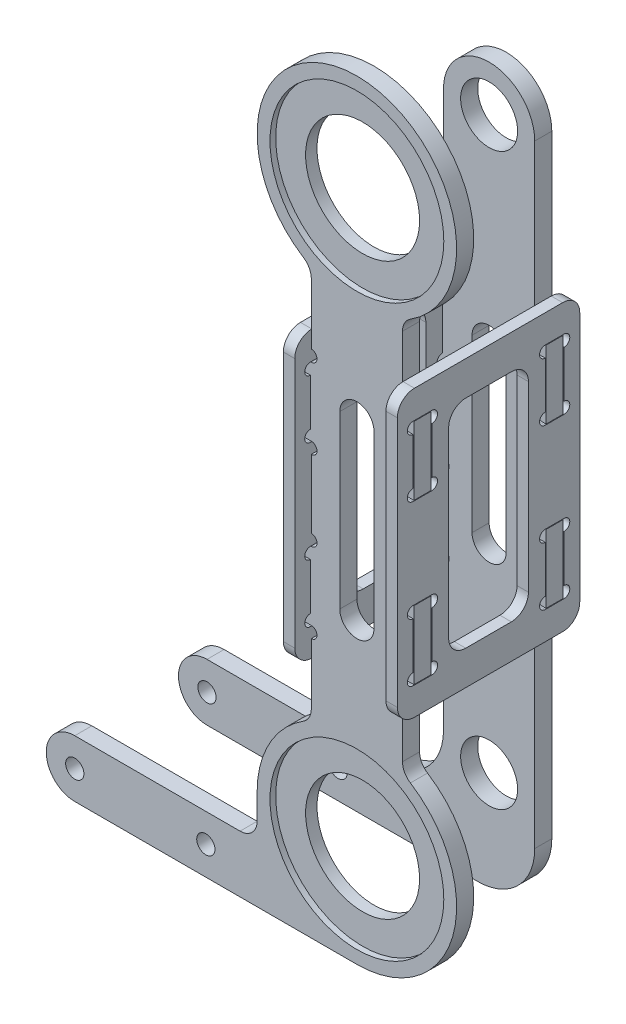
SolidWorks part; units mm, degrees
material "碳板"
ref_plane "前视基准面" through (0, 0, 0) normal (0, 0, 1) x (1, 0, 0)
ref_plane "上视基准面" through (0, 0, 0) normal (0, 1, 0) x (1, 0, 0)
ref_plane "右视基准面" through (0, 0, 0) normal (1, 0, 0) x (0, 0, -1)
sketch "草图1" plane through (0, 0, 0) normal (0, 0, 1) x (1, 0, 0)
  line L0 (-20.9655, 0) -> (46.7145, 0) construction
  line L1 (0, 28.1931) -> (0, -16.3862) construction
  line L2 (0, 5) -> (32, 5)
  line L3 (0, -5) -> (49.5, -5)
  line L4 (32, 5) -> (32, 12.5)
  line L5 (49.5, 12.5) -> (49.5, 117.1488) construction
  line L6 (41.5, 96.9356) -> (41.5, 84.5)
  line L7 (57.5, 96.9356) -> (57.5, 84.5)
  line L8 (41.5, 62.5) -> (57.5, 62.5) construction
  line L9 (41.5, 82.5) -> (39.5, 82.5)
  line L10 (39.5, 82.5) -> (39.5, 70.5)
  line L11 (39.5, 70.5) -> (41.5, 70.5)
  line L12 (49.5, 47.5) -> (49.5, 77.5) construction
  line L13 (41.5, 68.5) -> (41.5, 56.5)
  line L14 (59.5, 70.5) -> (57.5, 70.5)
  line L15 (59.5, 82.5) -> (59.5, 70.5)
  line L16 (57.5, 82.5) -> (59.5, 82.5)
  line L17 (39.5, 54.5) -> (41.5, 54.5)
  line L18 (39.5, 42.5) -> (39.5, 54.5)
  line L19 (41.5, 42.5) -> (39.5, 42.5)
  line L20 (59.5, 54.5) -> (57.5, 54.5)
  line L21 (59.5, 42.5) -> (59.5, 54.5)
  line L22 (57.5, 42.5) -> (59.5, 42.5)
  line L23 (46.5, 47.5) -> (46.5, 77.5)
  line L24 (41.5, 40.5) -> (41.5, 28.0644)
  line L25 (57.5, 68.5) -> (57.5, 56.5)
  line L26 (52.5, 47.5) -> (52.5, 77.5)
  line L28 (57.5, 40.5) -> (57.5, 28.0644)
  circle A0 centre (0, 0) radius 1.6
  circle A1 centre (23, 0) radius 1.6
  arc A2 (0, 5) -> (0, -5) centre (0, 0) ccw
  circle A3 centre (49.5, 12.5) radius 10
  arc A4 (41.5, 28.0644) -> (32, 12.5) centre (49.5, 12.5) ccw
  circle A5 centre (49.5, 112.5) radius 10
  arc A6 (57.5, 96.9356) -> (41.5, 96.9356) centre (49.5, 112.5) ccw
  arc A7 (41.5, 82.5) -> (41.5, 84.5) centre (41.5, 83.5) ccw
  arc A8 (41.5, 68.5) -> (41.5, 70.5) centre (41.5, 69.5) ccw
  arc A9 (57.5, 68.5) -> (57.5, 70.5) centre (57.5, 69.5) cw
  arc A10 (57.5, 82.5) -> (57.5, 84.5) centre (57.5, 83.5) cw
  arc A11 (41.5, 56.5) -> (41.5, 54.5) centre (41.5, 55.5) cw
  arc A12 (41.5, 42.5) -> (41.5, 40.5) centre (41.5, 41.5) cw
  arc A13 (57.5, 56.5) -> (57.5, 54.5) centre (57.5, 55.5) ccw
  arc A14 (57.5, 42.5) -> (57.5, 40.5) centre (57.5, 41.5) ccw
  arc A15 (49.5, -5) -> (57.5, 28.0644) centre (49.5, 12.5) ccw
  arc A16 (46.5, 47.5) -> (52.5, 47.5) centre (49.5, 47.5) ccw
  arc A17 (52.5, 77.5) -> (46.5, 77.5) centre (49.5, 77.5) ccw
  point P14 (49.5, 62.5)
  dimension "D1" = 3.2
  dimension "D3" = 10
  dimension "D5" = 20
  dimension "D6" = 35
  dimension "D11" = 2
  dimension "D2" = 23
  dimension "D4" = 32
  dimension "a" = 100
  dimension "D8" = 16
  dimension "D9" = 2
  dimension "D10" = 12
  dimension "D7" = 50
  dimension "D13" = 6
  dimension "D14" = 30
  dimension "D12" = 12
extrude "凸台-拉伸1" add sketch "草图1" along normal blind 3 from offset 10.1 contours A6 A5 | A6 L6 A4 L7 | A4 A3 | A4 L4 L2 A2 L3 A1 | A2 A0
sketch "草图6" plane through (0, 0, 13.1) normal (0, 0, 1) x (1, 0, 0)
  circle A0 centre (49.5, 112.5) radius 15.25
  circle A1 centre (49.5, 12.5) radius 15.25
  dimension "D1" = 30.5
  dimension "D2" = 30.5
extrude "切除-拉伸1" cut sketch "草图6" against normal blind 1
sketch "草图4" plane through (0, 0, 0) normal (0, 0, 1) x (1, 0, 0)
  line L0 (-12.4013, 0) -> (76.9383, 0) construction
  line L1 (0, -5) -> (49.5, -5) construction
  line L2 (0, -5) -> (49.5, -5)
  line L3 (57.5, 40.5) -> (57.5, 28.0644) construction
  line L4 (57.5, 40.5) -> (57.5, -3.0644)
  line L5 (41.5, 40.5) -> (41.5, 28.0644) construction
  line L6 (41.5, 40.5) -> (41.5, 5)
  line L7 (0, 5) -> (41.5, 5)
  line L8 (41.5, 42.5) -> (39.5, 42.5) construction
  line L9 (41.5, 42.5) -> (39.5, 42.5)
  line L10 (39.5, 42.5) -> (39.5, 54.5) construction
  line L11 (39.5, 42.5) -> (39.5, 54.5)
  line L12 (39.5, 54.5) -> (41.5, 54.5) construction
  line L13 (39.5, 54.5) -> (41.5, 54.5)
  line L14 (41.5, 68.5) -> (41.5, 56.5) construction
  line L15 (41.5, 68.5) -> (41.5, 56.5)
  line L16 (39.5, 70.5) -> (41.5, 70.5) construction
  line L17 (39.5, 70.5) -> (41.5, 70.5)
  line L18 (39.5, 82.5) -> (39.5, 70.5) construction
  line L19 (39.5, 82.5) -> (39.5, 70.5)
  line L20 (41.5, 82.5) -> (39.5, 82.5) construction
  line L21 (41.5, 82.5) -> (39.5, 82.5)
  line L22 (41.5, 96.9356) -> (41.5, 84.5) construction
  line L23 (41.5, 112.5) -> (41.5, 84.5)
  line L24 (57.5, 42.5) -> (59.5, 42.5) construction
  line L25 (57.5, 42.5) -> (59.5, 42.5)
  line L26 (59.5, 42.5) -> (59.5, 54.5) construction
  line L27 (59.5, 42.5) -> (59.5, 54.5)
  line L28 (59.5, 54.5) -> (57.5, 54.5) construction
  line L29 (59.5, 54.5) -> (57.5, 54.5)
  line L30 (57.5, 68.5) -> (57.5, 56.5) construction
  line L31 (57.5, 68.5) -> (57.5, 56.5)
  line L32 (59.5, 70.5) -> (57.5, 70.5) construction
  line L33 (59.5, 70.5) -> (57.5, 70.5)
  line L34 (59.5, 82.5) -> (59.5, 70.5) construction
  line L35 (59.5, 82.5) -> (59.5, 70.5)
  line L36 (57.5, 82.5) -> (59.5, 82.5) construction
  line L37 (57.5, 82.5) -> (59.5, 82.5)
  line L38 (57.5, 96.9356) -> (57.5, 84.5) construction
  line L39 (57.5, 112.5) -> (57.5, 84.5)
  line L40 (46.5, 47.5) -> (46.5, 77.5) construction
  line L41 (46.5, 47.5) -> (46.5, 77.5)
  line L42 (52.5, 47.5) -> (52.5, 77.5) construction
  line L43 (52.5, 47.5) -> (52.5, 77.5)
  circle A0 centre (0, 0) radius 1.6 construction
  circle A1 centre (0, 0) radius 1.6
  circle A2 centre (23, 0) radius 1.6 construction
  circle A3 centre (23, 0) radius 1.6
  arc A4 (0, 5) -> (0, -5) centre (0, 0) ccw construction
  arc A5 (0, 5) -> (0, -5) centre (0, 0) ccw
  arc A6 (49.5, -5) -> (57.5, 28.0644) centre (49.5, 12.5) ccw construction
  arc A7 (49.5, -5) -> (57.5, -3.0644) centre (49.5, 12.5) ccw
  circle A12 centre (49.5, 12.5) radius 5
  arc A13 (41.5, 40.5) -> (41.5, 42.5) centre (41.5, 41.5) ccw construction
  arc A14 (41.5, 40.5) -> (41.5, 42.5) centre (41.5, 41.5) ccw
  arc A15 (41.5, 54.5) -> (41.5, 56.5) centre (41.5, 55.5) ccw construction
  arc A16 (41.5, 54.5) -> (41.5, 56.5) centre (41.5, 55.5) ccw
  arc A17 (41.5, 68.5) -> (41.5, 70.5) centre (41.5, 69.5) ccw construction
  arc A18 (41.5, 68.5) -> (41.5, 70.5) centre (41.5, 69.5) ccw
  arc A19 (41.5, 82.5) -> (41.5, 84.5) centre (41.5, 83.5) ccw construction
  arc A20 (41.5, 82.5) -> (41.5, 84.5) centre (41.5, 83.5) ccw
  arc A21 (57.5, 42.5) -> (57.5, 40.5) centre (57.5, 41.5) ccw construction
  arc A22 (57.5, 42.5) -> (57.5, 40.5) centre (57.5, 41.5) ccw
  arc A23 (57.5, 56.5) -> (57.5, 54.5) centre (57.5, 55.5) ccw construction
  arc A24 (57.5, 56.5) -> (57.5, 54.5) centre (57.5, 55.5) ccw
  arc A25 (57.5, 70.5) -> (57.5, 68.5) centre (57.5, 69.5) ccw construction
  arc A26 (57.5, 70.5) -> (57.5, 68.5) centre (57.5, 69.5) ccw
  arc A27 (57.5, 84.5) -> (57.5, 82.5) centre (57.5, 83.5) ccw construction
  arc A28 (57.5, 84.5) -> (57.5, 82.5) centre (57.5, 83.5) ccw
  circle A29 centre (49.5, 112.5) radius 5
  arc A30 (57.5, 112.5) -> (41.5, 112.5) centre (49.5, 112.5) ccw
  arc A31 (52.5, 77.5) -> (46.5, 77.5) centre (49.5, 77.5) ccw construction
  arc A32 (52.5, 77.5) -> (46.5, 77.5) centre (49.5, 77.5) ccw
  arc A33 (46.5, 47.5) -> (52.5, 47.5) centre (49.5, 47.5) ccw construction
  arc A34 (46.5, 47.5) -> (52.5, 47.5) centre (49.5, 47.5) ccw
  dimension "D1" = 10
  dimension "D2" = 10
  dimension "D3" = 16
extrude "凸台-拉伸2" add sketch "草图4" against normal blind 3 from offset 10.1 separate body offset against normal yes
sketch "草图5" plane through (39.5, 0, 0) normal (-1, 0, 0) x (0, 0, 1)
  line L0 (0, 123.0583) -> (0, -20.4246) construction
  line L1 (-13.1, 76.5) -> (13.1, 76.5) construction
  line L2 (-13.1, 82.5) -> (-13.1, 70.5) construction
  line L3 (13.1, 82.5) -> (13.1, 70.5) construction
  line L4 (-10.1, 68.5) -> (-10.1, 56.5) construction
  line L5 (-10.1, 68.5) -> (-10.1, 56.5) construction
  line L6 (-10.1, 62.5) -> (0, 62.5) construction
  line L7 (-11.6, 82.5) -> (-11.6, 70.5) construction
  line L8 (-13.1, 82.5) -> (-10.1, 82.5) construction
  line L9 (-13.1, 70.5) -> (-10.1, 70.5) construction
  line L10 (13.25, 80.6) -> (13.25, 72.4)
  line L11 (-13.25, 82.6) -> (-9.95, 82.6)
  line L12 (-13.25, 80.6) -> (-13.25, 72.4)
  line L13 (-13.25, 70.4) -> (-9.95, 70.4)
  line L14 (-9.95, 80.6) -> (-9.95, 72.4)
  line L15 (-13.25, 82.6) -> (-9.95, 70.4) construction
  line L16 (-13.25, 70.4) -> (-9.95, 82.6) construction
  line L17 (13.25, 70.4) -> (9.95, 70.4)
  line L18 (9.95, 80.6) -> (9.95, 72.4)
  line L19 (13.25, 82.6) -> (9.95, 82.6)
  line L20 (-13.25, 44.4) -> (-13.25, 52.6)
  line L21 (-13.25, 54.6) -> (-9.95, 54.6)
  line L22 (-9.95, 44.4) -> (-9.95, 52.6)
  line L23 (-13.25, 42.4) -> (-9.95, 42.4)
  line L24 (13.25, 42.4) -> (9.95, 42.4)
  line L25 (9.95, 44.4) -> (9.95, 52.6)
  line L26 (13.25, 54.6) -> (9.95, 54.6)
  line L27 (13.25, 44.4) -> (13.25, 52.6)
  line L29 (-16, 87.5) -> (16, 87.5)
  line L30 (-16, 87.5) -> (-16, 37.5)
  line L31 (-16, 37.5) -> (16, 37.5)
  line L32 (16, 87.5) -> (16, 37.5)
  line L33 (-16, 87.5) -> (16, 37.5) construction
  line L34 (-16, 37.5) -> (16, 87.5) construction
  line L35 (-7, 81.5) -> (7, 81.5)
  line L36 (-7, 81.5) -> (-7, 43.5)
  line L37 (-7, 43.5) -> (7, 43.5)
  line L38 (7, 81.5) -> (7, 43.5)
  line L39 (-7, 81.5) -> (7, 43.5) construction
  line L40 (-7, 43.5) -> (7, 81.5) construction
  arc A0 (-13.25, 82.6) -> (-13.25, 80.6) centre (-13.25, 81.6) ccw
  arc A1 (-9.95, 80.6) -> (-9.95, 82.6) centre (-9.95, 81.6) ccw
  arc A2 (-13.25, 72.4) -> (-13.25, 70.4) centre (-13.25, 71.4) ccw
  arc A3 (-9.95, 70.4) -> (-9.95, 72.4) centre (-9.95, 71.4) ccw
  arc A4 (13.25, 82.6) -> (13.25, 80.6) centre (13.25, 81.6) cw
  arc A5 (13.25, 72.4) -> (13.25, 70.4) centre (13.25, 71.4) cw
  arc A6 (9.95, 70.4) -> (9.95, 72.4) centre (9.95, 71.4) cw
  arc A7 (9.95, 80.6) -> (9.95, 82.6) centre (9.95, 81.6) cw
  arc A8 (-13.25, 42.4) -> (-13.25, 44.4) centre (-13.25, 43.4) cw
  arc A9 (-13.25, 52.6) -> (-13.25, 54.6) centre (-13.25, 53.6) cw
  arc A10 (-9.95, 54.6) -> (-9.95, 52.6) centre (-9.95, 53.6) cw
  arc A11 (-9.95, 44.4) -> (-9.95, 42.4) centre (-9.95, 43.4) cw
  arc A12 (9.95, 44.4) -> (9.95, 42.4) centre (9.95, 43.4) ccw
  arc A13 (9.95, 54.6) -> (9.95, 52.6) centre (9.95, 53.6) ccw
  arc A14 (13.25, 52.6) -> (13.25, 54.6) centre (13.25, 53.6) ccw
  arc A15 (13.25, 42.4) -> (13.25, 44.4) centre (13.25, 43.4) ccw
  point P19 (-11.6, 76.5)
  dimension "D3" = 2
  dimension "D1" = 3.3
  dimension "D2" = 12.2
  dimension "D4" = 32
  dimension "D5" = 50
  dimension "D6" = 6
  dimension "D7" = 9
extrude "凸台-拉伸3" add sketch "草图5" against normal blind 2 separate body
fillet "圆角1" radius 3 5 edges at (41.5, 96.9356, 11.6) (57.5, 96.9356, 11.6) (57.5, 28.0644, 11.6) (41.5, 28.0644, 11.6) (32, 5, 11.6)
fillet "圆角2" radius 10 2 edges at (41.5, 5, -11.6) (57.5, -3.0644, -11.6)
fillet "圆角3" radius 3 8 edges at (40.5, 81.5, -7) (40.5, 81.5, 7) (40.5, 43.5, 7) (40.5, 43.5, -7) (40.5, 87.5, 16) (40.5, 87.5, -16) (40.5, 37.5, -16) (40.5, 37.5, 16)
ref_plane "基准面1" through (49.5, 0, 0) normal (-1, 0, 0) x (0, 0, 1)
mirror "镜向1" about plane through (49.5, 0, 0) normal (-1, 0, 0) of bodies 108
equation "\"D7@草图1\"= \"a\" * 0.5"
